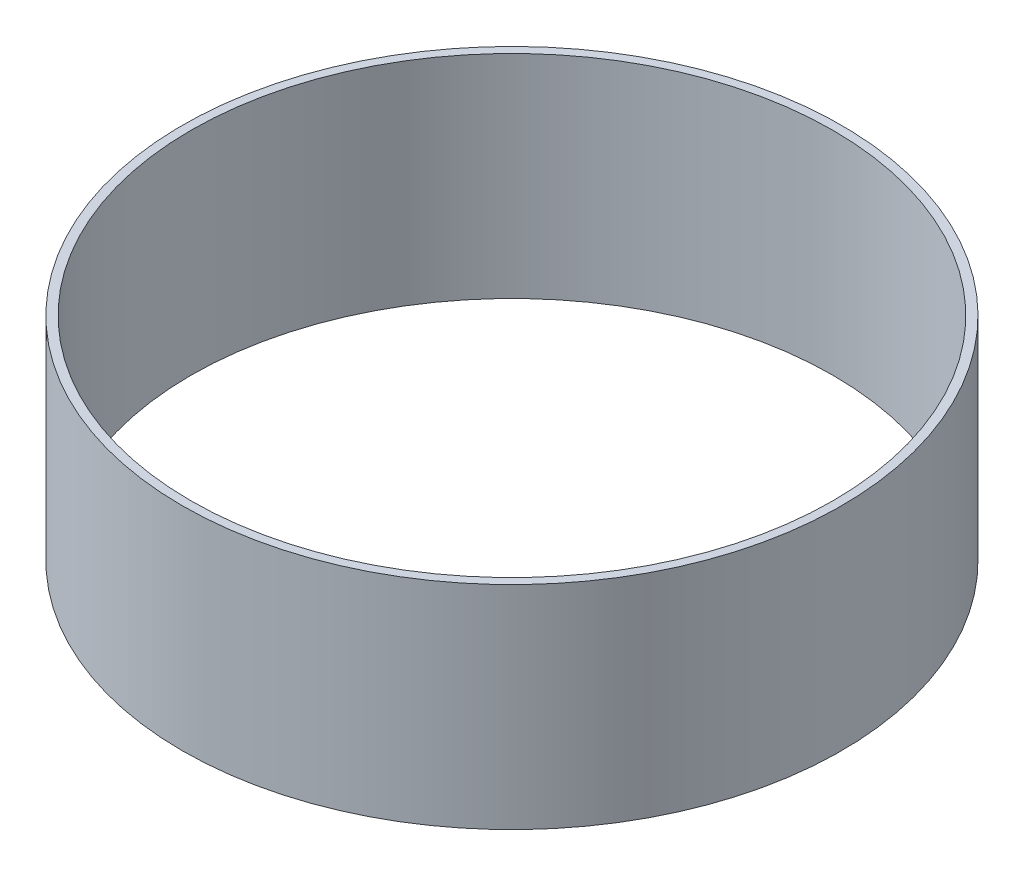
SolidWorks part; units mm, degrees
ref_plane "Front Plane" through (0, 0, 0) normal (0, 0, 1) x (1, 0, 0)
ref_plane "Top Plane" through (0, 0, 0) normal (0, 1, 0) x (1, 0, 0)
ref_plane "Right Plane" through (0, 0, 0) normal (1, 0, 0) x (0, 0, -1)
sketch "Sketch1" plane through (0, 0, 0) normal (0, 1, 0) x (1, 0, 0)
  circle A0 centre (0, 0) radius 24.2
  circle A1 centre (0, 0) radius 24.85
  dimension "D1" = 48.4
  dimension "D2" = 49.7
extrude "Boss-Extrude1" add sketch "Sketch1" along normal blind 16
